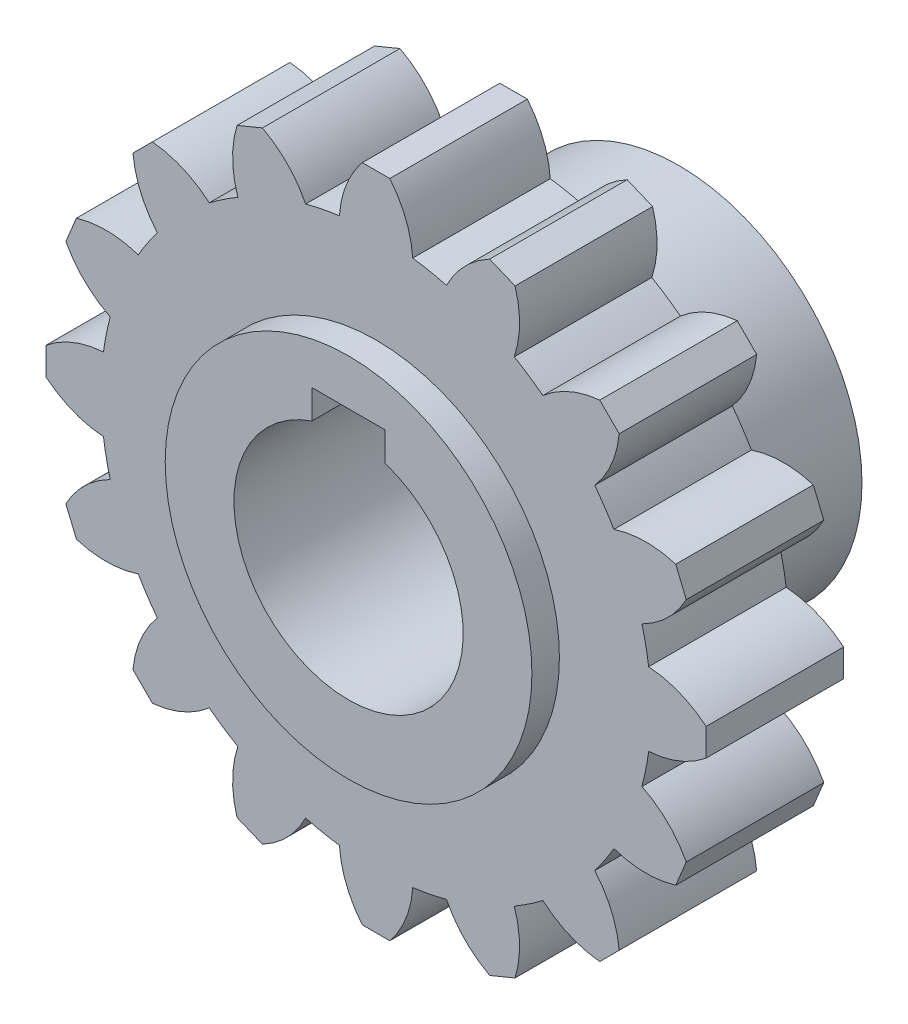
SolidWorks part; units mm, degrees
ref_plane "Front Plane" through (0, 0, 0) normal (0, 0, 1) x (1, 0, 0)
ref_plane "Top Plane" through (0, 0, 0) normal (0, 1, 0) x (1, 0, 0)
ref_plane "Right Plane" through (0, 0, 0) normal (1, 0, 0) x (0, 0, -1)
sketch "Sketch1" plane through (0, 0, 0) normal (0, 0, 1) x (1, 0, 0)
  circle A0 centre (0, 0) radius 30
  dimension "D1" = 60
extrude "Boss-Extrude1" add sketch "Sketch1" along normal blind 15
sketch "Sketch2" plane through (0, 0, 15) normal (0, 0, 1) x (1, 0, 0)
  circle A0 centre (0, 0) radius 20
  dimension "D1" = 40
extrude "Boss-Extrude2" add sketch "Sketch2" along normal blind 3
sketch "Sketch3" plane through (0, 0, 0) normal (0, 0, -1) x (-1, 0, 0)
  circle A0 centre (0, 0) radius 20
  dimension "D1" = 40
extrude "Boss-Extrude3" add sketch "Sketch3" along normal blind 18
sketch "Sketch4" plane through (0, 0, -18) normal (0, 0, -1) x (-1, 0, 0)
  line L1 (-4, 15) -> (4, 15)
  line L2 (-4, 15) -> (-4, 11.8427)
  line L4 (4, 15) -> (4, 11.8427)
  arc A0 (-4, 11.8427) -> (4, 11.8427) centre (0, 0) ccw
  dimension "D1" = 25
  dimension "D2" = 15
  dimension "D3" = 8
  dimension "D4" = 4
extrude "Cut-Extrude1" cut sketch "Sketch4" against normal through all
ref_plane "Plane1" through (0, 0, 7.5) normal (0, 0, 1) x (1, 0, 0)
sketch "Sketch5" plane through (0, 0, 7.5) normal (0, 0, 1) x (1, 0, 0)
  line L0 (0, 43.9736) -> (0, -41.8093) construction
  line L1 (-1.5, 36) -> (1.5, 36)
  line L2 (0, 30) -> (16.1042, 30) construction
  line L3 (12.3908, 33.8337) -> (15.1624, 32.6856)
  line L4 (24.3952, 26.5165) -> (26.5165, 24.3952)
  line L5 (32.6856, 15.1624) -> (33.8337, 12.3908)
  line L6 (36, 1.5) -> (36, -1.5)
  line L7 (33.8337, -12.3908) -> (32.6856, -15.1624)
  line L8 (26.5165, -24.3952) -> (24.3952, -26.5165)
  line L9 (15.1624, -32.6856) -> (12.3908, -33.8337)
  line L10 (1.5, -36) -> (-1.5, -36)
  line L11 (-12.3908, -33.8337) -> (-15.1624, -32.6856)
  line L12 (-24.3952, -26.5165) -> (-26.5165, -24.3952)
  line L13 (-32.6856, -15.1624) -> (-33.8337, -12.3908)
  line L14 (-36, -1.5) -> (-36, 1.5)
  line L15 (-33.8337, 12.3908) -> (-32.6856, 15.1624)
  line L16 (-26.5165, 24.3952) -> (-24.3952, 26.5165)
  line L17 (-15.1624, 32.6856) -> (-12.3908, 33.8337)
  arc A0 (-1.5, 36) -> (-4, 29.7321) centre (6.9748, 28.9873) ccw
  circle A1 centre (0, 0) radius 30 construction
  arc A2 (1.5, 36) -> (4, 29.7321) centre (-6.9748, 28.9873) cw
  arc A3 (-4, 29.7321) -> (4, 29.7321) centre (0, 0) cw
  arc A4 (7.6825, 28.9996) -> (15.0735, 25.9382) centre (0, 0) cw
  arc A5 (15.1624, 32.6856) -> (15.0735, 25.9382) centre (4.6491, 29.4499) cw
  arc A6 (12.3908, 33.8337) -> (7.6825, 28.9996) centre (17.5368, 24.1116) ccw
  arc A7 (18.1954, 23.8522) -> (23.8522, 18.1954) centre (0, 0) cw
  arc A8 (26.5165, 24.3952) -> (23.8522, 18.1954) centre (15.5652, 25.429) cw
  arc A9 (24.3952, 26.5165) -> (18.1954, 23.8522) centre (25.429, 15.5652) ccw
  arc A10 (25.9382, 15.0735) -> (28.9996, 7.6825) centre (0, 0) cw
  arc A11 (33.8337, 12.3908) -> (28.9996, 7.6825) centre (24.1116, 17.5368) cw
  arc A12 (32.6856, 15.1624) -> (25.9382, 15.0735) centre (29.4499, 4.6491) ccw
  arc A13 (29.7321, 4) -> (29.7321, -4) centre (0, 0) cw
  arc A14 (36, -1.5) -> (29.7321, -4) centre (28.9873, 6.9748) cw
  arc A15 (36, 1.5) -> (29.7321, 4) centre (28.9873, -6.9748) ccw
  arc A16 (28.9996, -7.6825) -> (25.9382, -15.0735) centre (0, 0) cw
  arc A17 (32.6856, -15.1624) -> (25.9382, -15.0735) centre (29.4499, -4.6491) cw
  arc A18 (33.8337, -12.3908) -> (28.9996, -7.6825) centre (24.1116, -17.5368) ccw
  arc A19 (23.8522, -18.1954) -> (18.1954, -23.8522) centre (0, 0) cw
  arc A20 (24.3952, -26.5165) -> (18.1954, -23.8522) centre (25.429, -15.5652) cw
  arc A21 (26.5165, -24.3952) -> (23.8522, -18.1954) centre (15.5652, -25.429) ccw
  arc A22 (15.0735, -25.9382) -> (7.6825, -28.9996) centre (0, 0) cw
  arc A23 (12.3908, -33.8337) -> (7.6825, -28.9996) centre (17.5368, -24.1116) cw
  arc A24 (15.1624, -32.6856) -> (15.0735, -25.9382) centre (4.6491, -29.4499) ccw
  arc A25 (4, -29.7321) -> (-4, -29.7321) centre (0, 0) cw
  arc A26 (-1.5, -36) -> (-4, -29.7321) centre (6.9748, -28.9873) cw
  arc A27 (1.5, -36) -> (4, -29.7321) centre (-6.9748, -28.9873) ccw
  arc A28 (-7.6825, -28.9996) -> (-15.0735, -25.9382) centre (0, 0) cw
  arc A29 (-15.1624, -32.6856) -> (-15.0735, -25.9382) centre (-4.6491, -29.4499) cw
  arc A30 (-12.3908, -33.8337) -> (-7.6825, -28.9996) centre (-17.5368, -24.1116) ccw
  arc A31 (-18.1954, -23.8522) -> (-23.8522, -18.1954) centre (0, 0) cw
  arc A32 (-26.5165, -24.3952) -> (-23.8522, -18.1954) centre (-15.5652, -25.429) cw
  arc A33 (-24.3952, -26.5165) -> (-18.1954, -23.8522) centre (-25.429, -15.5652) ccw
  arc A34 (-25.9382, -15.0735) -> (-28.9996, -7.6825) centre (0, 0) cw
  arc A35 (-33.8337, -12.3908) -> (-28.9996, -7.6825) centre (-24.1116, -17.5368) cw
  arc A36 (-32.6856, -15.1624) -> (-25.9382, -15.0735) centre (-29.4499, -4.6491) ccw
  arc A37 (-29.7321, -4) -> (-29.7321, 4) centre (0, 0) cw
  arc A38 (-36, 1.5) -> (-29.7321, 4) centre (-28.9873, -6.9748) cw
  arc A39 (-36, -1.5) -> (-29.7321, -4) centre (-28.9873, 6.9748) ccw
  arc A40 (-28.9996, 7.6825) -> (-25.9382, 15.0735) centre (0, 0) cw
  arc A41 (-32.6856, 15.1624) -> (-25.9382, 15.0735) centre (-29.4499, 4.6491) cw
  arc A42 (-33.8337, 12.3908) -> (-28.9996, 7.6825) centre (-24.1116, 17.5368) ccw
  arc A43 (-23.8522, 18.1954) -> (-18.1954, 23.8522) centre (0, 0) cw
  arc A44 (-24.3952, 26.5165) -> (-18.1954, 23.8522) centre (-25.429, 15.5652) cw
  arc A45 (-26.5165, 24.3952) -> (-23.8522, 18.1954) centre (-15.5652, 25.429) ccw
  arc A46 (-15.0735, 25.9382) -> (-7.6825, 28.9996) centre (0, 0) cw
  arc A47 (-12.3908, 33.8337) -> (-7.6825, 28.9996) centre (-17.5368, 24.1116) cw
  arc A48 (-15.1624, 32.6856) -> (-15.0735, 25.9382) centre (-4.6491, 29.4499) ccw
  point P12 (0, 36)
  point P107 (0, 0)
  dimension "D1" = 1.5
  dimension "D2" = 11
  dimension "D3" = 6
  dimension "D5" = 16
  dimension "D4" = 4
extrude "Boss-Extrude5" add sketch "Sketch5" along normal mid plane 15
